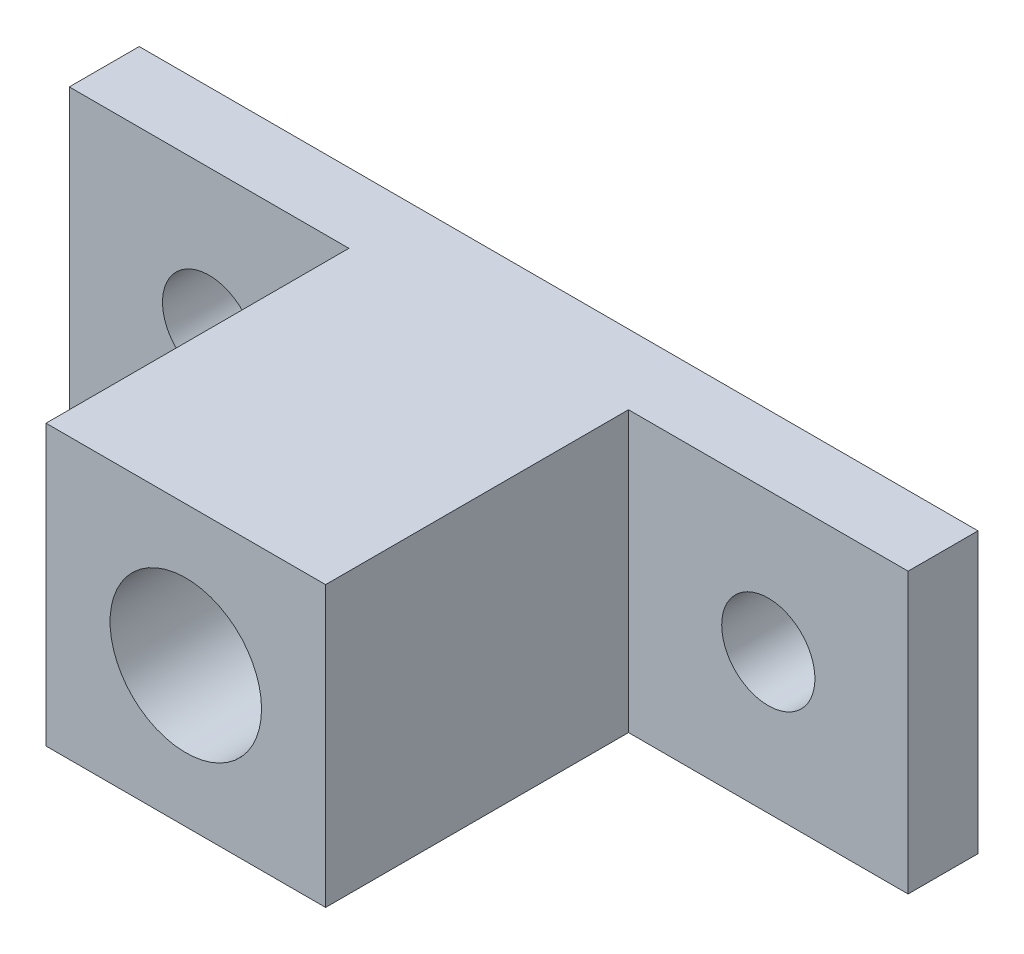
SolidWorks part; units mm, degrees
ref_plane "Alzado" through (0, 0, 0) normal (0, 0, 1) x (1, 0, 0)
ref_plane "Planta" through (0, 0, 0) normal (0, 1, 0) x (1, 0, 0)
ref_plane "Vista lateral" through (0, 0, 0) normal (1, 0, 0) x (0, 0, -1)
sketch "Croquis1" plane through (0, 0, 0) normal (0, 0, 1) x (1, 0, 0)
  line L1 (-18, -6) -> (18, -6)
  line L2 (-18, -6) -> (-18, 6)
  line L3 (-18, 6) -> (18, 6)
  line L4 (18, -6) -> (18, 6)
  line L5 (-18, -6) -> (18, 6) construction
  line L6 (-18, 6) -> (18, -6) construction
  point P0 (0, 0)
  dimension "D1" = 36
  dimension "D2" = 12
extrude "Saliente-Extruir1" add sketch "Croquis1" along normal mid plane 16
sketch "Croquis2" plane through (0, 0, 8) normal (0, 0, 1) x (1, 0, 0)
  circle A0 centre (0, 0) radius 3.25
  dimension "D1" = 6.5
extrude "Cortar-Extruir1" cut sketch "Croquis2" against normal blind 8
sketch "Croquis3" plane through (0, -6, 0) normal (0, -1, 0) x (1, 0, 0)
  line L0 (0, 6.7031) -> (0, -9.4375) construction
  line L1 (-18, 8) -> (-18, -8) construction
  line L2 (-18, -5) -> (-6, -5)
  line L3 (-18, -5) -> (-18, 8)
  line L4 (-18, 8) -> (-6, 8)
  line L5 (-6, -5) -> (-6, 8)
  line L6 (-18, 8) -> (18, 8) construction
  line L7 (-18, -8) -> (18, -8) construction
  line L8 (18, 8) -> (6, 8)
  line L9 (6, -5) -> (6, 8)
  line L10 (18, -5) -> (6, -5)
  line L11 (18, -5) -> (18, 8)
  dimension "D1" = 12
  dimension "D2" = 3
extrude "Cortar-Extruir2" cut sketch "Croquis3" against normal through all
sketch "Croquis4" plane through (0, 0, -5) normal (0, 0, 1) x (1, 0, 0)
  line L0 (-12, 6) -> (-12, -6) construction
  line L1 (0, 6) -> (0, -6) construction
  line L2 (6, 6) -> (-6, 6) construction
  line L3 (-6, -6) -> (6, -6) construction
  line L4 (-18, -6) -> (-6, -6)
  line L5 (-6, -6) -> (-6, 6)
  line L6 (-6, 6) -> (-18, 6)
  line L7 (-18, 6) -> (-18, -6)
  line L8 (-18, -6) -> (-6, -6) construction
  line L9 (-6, -6) -> (-6, 6) construction
  line L10 (-6, 6) -> (-18, 6) construction
  line L11 (-18, 6) -> (-18, -6) construction
  circle A0 centre (-12, 0) radius 2
  circle A1 centre (12, 0) radius 2
  dimension "D2" = 4
  dimension "D1" = 0
extrude "Cortar-Extruir3" cut sketch "Croquis4" against normal blind 8
